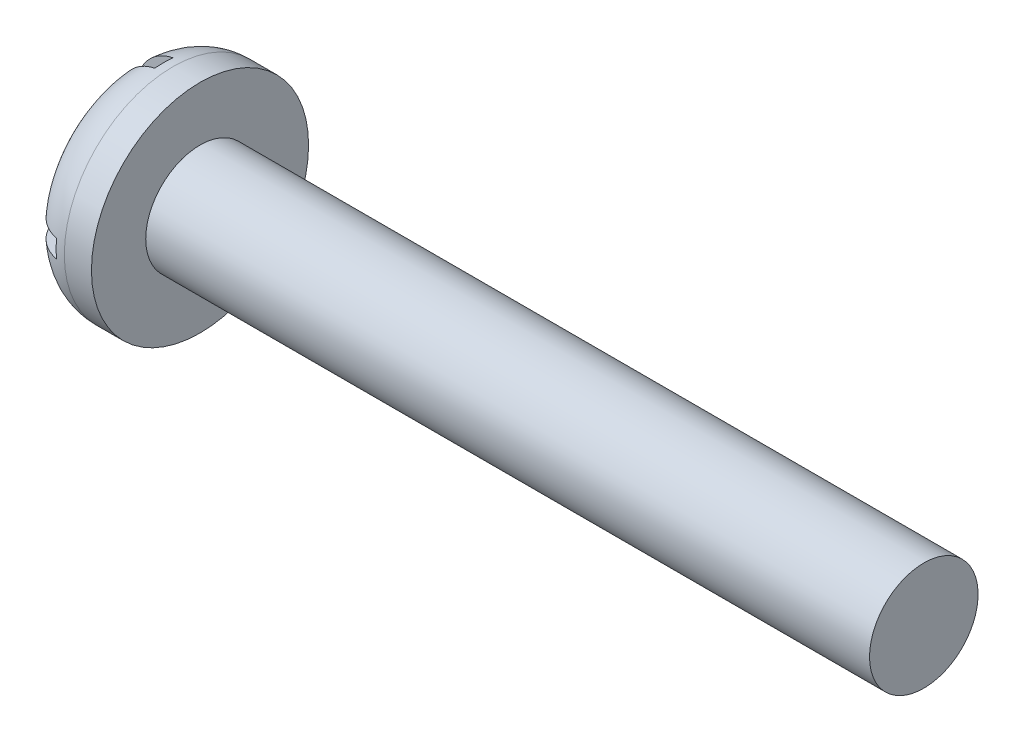
SolidWorks part; units mm, degrees
ref_plane "Спереди" through (0, 0, 0) normal (0, 0, 1) x (1, 0, 0)
ref_plane "Сверху" through (0, 0, 0) normal (0, 1, 0) x (1, 0, 0)
ref_plane "Справа" through (0, 0, 0) normal (1, 0, 0) x (0, 0, -1)
sketch "Эскиз1" plane through (0, 0, 0) normal (0, 0, 1) x (1, 0, 0)
  line L0 (-40.2764, 0) -> (78.2996, 0) construction
  line L1 (0, 0) -> (44, 0)
  line L3 (0, 0) -> (0, 3.5)
  line L4 (2.5, 6) -> (4, 6)
  line L5 (4, 3) -> (4, 6)
  line L8 (4, 3) -> (44, 3)
  line L9 (44, 0) -> (44, 3)
  arc A0 (0, 3.5) -> (2.5, 6) centre (2.5, 3.5) cw
  point P11 (0, 6)
  dimension "D6" = 2.5
  dimension "D1" = 6
  dimension "D2" = 3
  dimension "D3" = 6
  dimension "D4" = 4
  dimension "D5" = 40
revolve "Повернуть1" add sketch "Эскиз1" angle 360 about L0
sketch "Эскиз2" plane through (0, 0, 0) normal (-1, 0, 0) x (0, 0, 1)
  line L0 (0, 6.7576) -> (0, -6.7402) construction
  line L1 (-6.9402, 0) -> (6.7141, 0) construction
  line L2 (-0.5, -6.862) -> (0.5, -6.862)
  line L3 (-0.5, -6.862) -> (-0.5, -0.5)
  line L4 (-0.5, 7.0707) -> (0.5, 7.0707)
  line L5 (0.5, -6.862) -> (0.5, -0.5)
  line L6 (0.5, 0.5) -> (0.5, 7.0707)
  line L7 (-7.4968, -0.5) -> (-0.5, -0.5)
  line L8 (-7.4968, -0.5) -> (-7.4968, 0.5)
  line L9 (-7.4968, 0.5) -> (-0.5, 0.5)
  line L10 (7.7056, -0.5) -> (7.7056, 0.5)
  line L11 (0.5, -0.5) -> (7.7056, -0.5)
  line L12 (-0.5, 0.5) -> (-0.5, 7.0707)
  line L13 (0.5, 0.5) -> (7.7056, 0.5)
  dimension "D1" = 1
  dimension "D2" = 1
extrude "Вырез-Вытянуть1" cut sketch "Эскиз2" against normal blind 2
